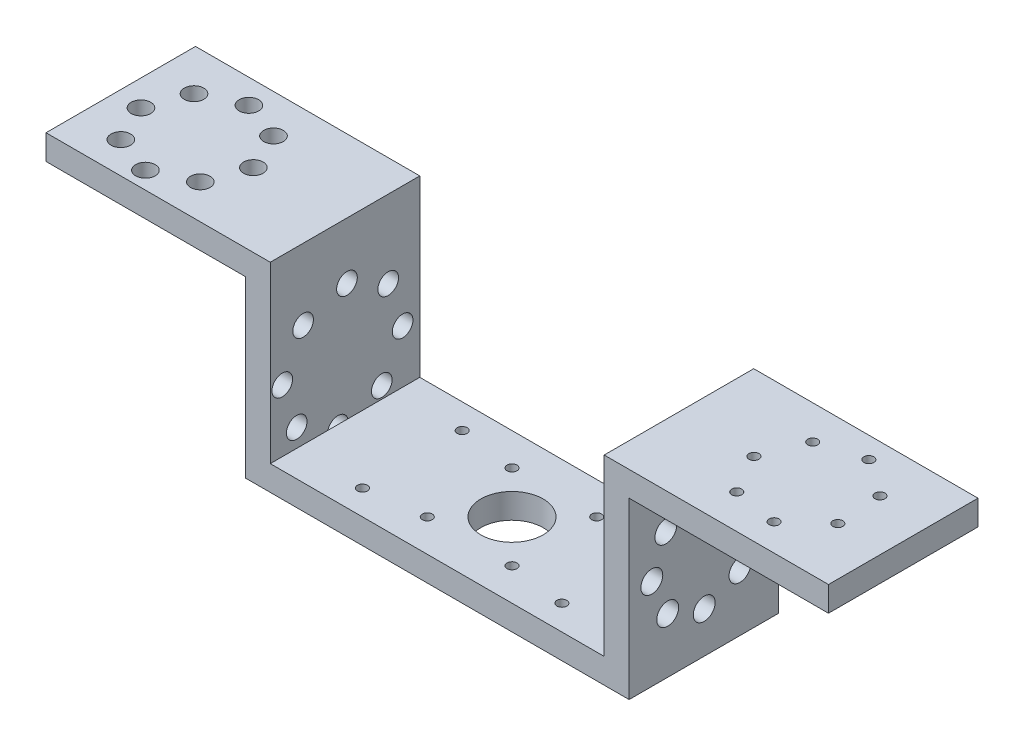
SolidWorks part; units mm, degrees
ref_plane "Front Plane" through (0, 0, 0) normal (0, 0, 1) x (1, 0, 0)
ref_plane "Top Plane" through (0, 0, 0) normal (0, 1, 0) x (1, 0, 0)
ref_plane "Right Plane" through (0, 0, 0) normal (1, 0, 0) x (0, 0, -1)
sketch "Sketch1" plane through (0, 0, 0) normal (0, 1, 0) x (1, 0, 0)
  line L1 (0, 0) -> (67, 0)
  line L2 (0, 0) -> (0, 30)
  line L3 (0, 30) -> (67, 30)
  line L4 (67, 0) -> (67, 30)
  circle A0 centre (33.5, 15) radius 6.25
  circle A1 centre (42, 23.5) radius 1
  circle A2 centre (42, 6.5) radius 1
  circle A3 centre (25, 6.5) radius 1
  circle A4 centre (25, 23.5) radius 1
  circle A5 centre (53.5, 5) radius 1
  circle A6 centre (53.5, 25) radius 1
  circle A7 centre (13.5, 25) radius 1
  circle A8 centre (13.5, 5) radius 1
  point P8 (67, 15)
  point P9 (33.5, 30)
  dimension "D5" = 12.5
  dimension "D8" = 2
  dimension "D1" = 67
  dimension "D2" = 30
  dimension "D3" = 33.5
  dimension "D4" = 15
  dimension "D6" = 17
  dimension "D7" = 17
  dimension "D9" = 40
  dimension "D10" = 20
sketch "Sketch2" plane through (0, 0, 0) normal (1, 0, 0) x (0, 0, -1)
  line L0 (0, 0) -> (30, 0) construction
  line L1 (0, 0) -> (30, 0) construction
  line L2 (30, 0) -> (0, 0)
  line L3 (30, 0) -> (30, 40)
  line L5 (0, 0) -> (0, 40)
  line L6 (0, 40) -> (7.9606, 40)
  line L7 (30, 40) -> (20.9763, 40)
  arc A0 (20.9763, 40) -> (7.9606, 40) centre (14.4684, 37.1176) cw
  circle A1 centre (14.4684, 24.2386) radius 2.2461
  circle A2 centre (6.5789, 27.6528) radius 2.2461
  circle A3 centre (3.4144, 35.6458) radius 2.2461
  circle A7 centre (25.8756, 35.2927) radius 2.2461
  circle A8 centre (22.4614, 27.4032) radius 2.2461
  circle A9 centre (14.8215, 46.6998) radius 2.2461 [skipped]
  circle A10 centre (6.8286, 43.5353) radius 2.2461 [skipped]
  circle A11 centre (22.711, 43.2856) radius 2.2461 [skipped]
  point P11 (14.4684, 30)
  point P31 (14.645, 35.4692)
  dimension "D1" = 40
  dimension "D2" = 10
  dimension "D3" = 10
  dimension "D4" = 8
extrude "Boss-Extrude1" add sketch "Sketch2" against normal blind 5
extrude "Boss-Extrude3" add sketch "Sketch1" along normal blind 5
ref_plane "Plane1" through (33.5, 0, 0) normal (1, 0, 0) x (0, 0, -1)
mirror "Mirror1" about plane through (33.5, 0, 0) normal (1, 0, 0) of "Boss-Extrude1"
sketch "Sketch8" plane through (-5, 0, 0) normal (-1, 0, 0) x (0, 0, 1)
  line L0 (-30, 0) -> (-30, 40) construction
  line L1 (-30, 40) -> (0, 40)
  line L2 (-30, 40) -> (-30, 0)
  line L3 (-30, 0) -> (0, 0)
  line L4 (0, 40) -> (0, 0)
extrude "Boss-Extrude4" add sketch "Sketch8" against normal blind 5
sketch "Sketch9" plane through (72, 0, 0) normal (1, 0, 0) x (0, 0, -1)
  line L1 (0, 40) -> (30, 40)
  line L2 (0, 40) -> (0, 0)
  line L3 (0, 0) -> (30, 0)
  line L4 (30, 40) -> (30, 0)
extrude "Boss-Extrude5" add sketch "Sketch9" against normal blind 5
sketch "Sketch11" plane through (72, 0, 0) normal (1, 0, 0) x (0, 0, -1)
  line L0 (30, 0) -> (30, 40) construction
  line L1 (0, 40) -> (30, 40)
  line L6 (0, 40) -> (0, 35)
  line L7 (0, 35) -> (30, 35)
  line L8 (30, 40) -> (30, 35)
  dimension "D1" = 5
extrude "Boss-Extrude6" add sketch "Sketch11" along normal blind 40
sketch "Sketch12" plane through (-5, 0, 0) normal (-1, 0, 0) x (0, 0, 1)
  line L0 (-30, 0) -> (-30, 40) construction
  line L2 (-30, 35) -> (0, 35)
  line L3 (-30, 35) -> (-30, 40)
  line L4 (-30, 40) -> (0, 40)
  line L5 (0, 35) -> (0, 40)
  dimension "D1" = 5
extrude "Boss-Extrude7" add sketch "Sketch12" along normal blind 40
sketch "Sketch13" plane through (72, 0, 0) normal (1, 0, 0) x (0, 0, -1)
  circle A0 centre (4.5521, 18.2468) radius 2.1959
  circle A1 centre (7.7388, 11.0727) radius 2.1959
  circle A2 centre (15.0649, 8.2532) radius 2.1959
  circle A3 centre (22.239, 11.4398) radius 2.1959
  circle A4 centre (25.0585, 18.766) radius 2.1959
  circle A5 centre (21.8719, 25.94) radius 2.1959
  circle A6 centre (14.5457, 28.7596) radius 2.1959
  circle A7 centre (7.3717, 25.5729) radius 2.1959
  point P18 (14.8053, 18.5064)
  dimension "D1" = 8
extrude "Cut-Extrude1" cut sketch "Sketch13" against normal blind 5
sketch "Sketch14" plane through (0, 35, 0) normal (0, -1, 0) x (1, 0, 0)
  circle A0 centre (82.2656, -14.7778) radius 1
  circle A1 centre (85.6662, -23.1702) radius 1
  circle A2 centre (94.3479, -25.7441) radius 1
  circle A3 centre (101.7731, -20.5613) radius 1
  circle A4 centre (102.3506, -11.5246) radius 1
  circle A5 centre (95.6455, -5.4388) radius 1
  circle A6 centre (86.7068, -6.8866) radius 1
  point P17 (92.6794, -15.4434)
  dimension "D1" = 2
  dimension "D2" = 7
extrude "Cut-Extrude2" cut sketch "Sketch14" against normal blind 5
sketch "Sketch15" plane through (-5, 0, 0) normal (-1, 0, 0) x (0, 0, 1)
  circle A0 centre (-15.3894, 28.6298) radius 2.0705
  circle A1 centre (-23.6582, 24.4521) radius 2.0705
  circle A2 centre (-26.5511, 15.6511) radius 2.0705
  circle A3 centre (-22.3734, 7.3822) radius 2.0705
  circle A4 centre (-13.5723, 4.4893) radius 2.0705
  circle A5 centre (-5.3035, 8.667) radius 2.0705
  circle A6 centre (-2.4106, 17.4681) radius 2.0705
  circle A7 centre (-6.5883, 25.7369) radius 2.0705
  point P19 (-14.4809, 16.5596)
  dimension "D1" = 8
extrude "Cut-Extrude3" cut sketch "Sketch15" against normal blind 5
sketch "Sketch16" plane through (0, 35, 0) normal (0, -1, 0) x (1, 0, 0)
  circle A0 centre (-39.7862, -13.8417) radius 1.9627
  circle A1 centre (-36.2982, -6.3158) radius 1.9627
  circle A2 centre (-28.5102, -3.4606) radius 1.9627
  circle A3 centre (-20.9843, -6.9486) radius 1.9627
  circle A4 centre (-18.1291, -14.7366) radius 1.9627
  circle A5 centre (-21.6171, -22.2625) radius 1.9627
  circle A6 centre (-29.4051, -25.1177) radius 1.9627
  circle A7 centre (-36.931, -21.6297) radius 1.9627
  point P18 (-28.9577, -14.2891)
  dimension "D1" = 8
extrude "Cut-Extrude4" cut sketch "Sketch16" against normal blind 5
